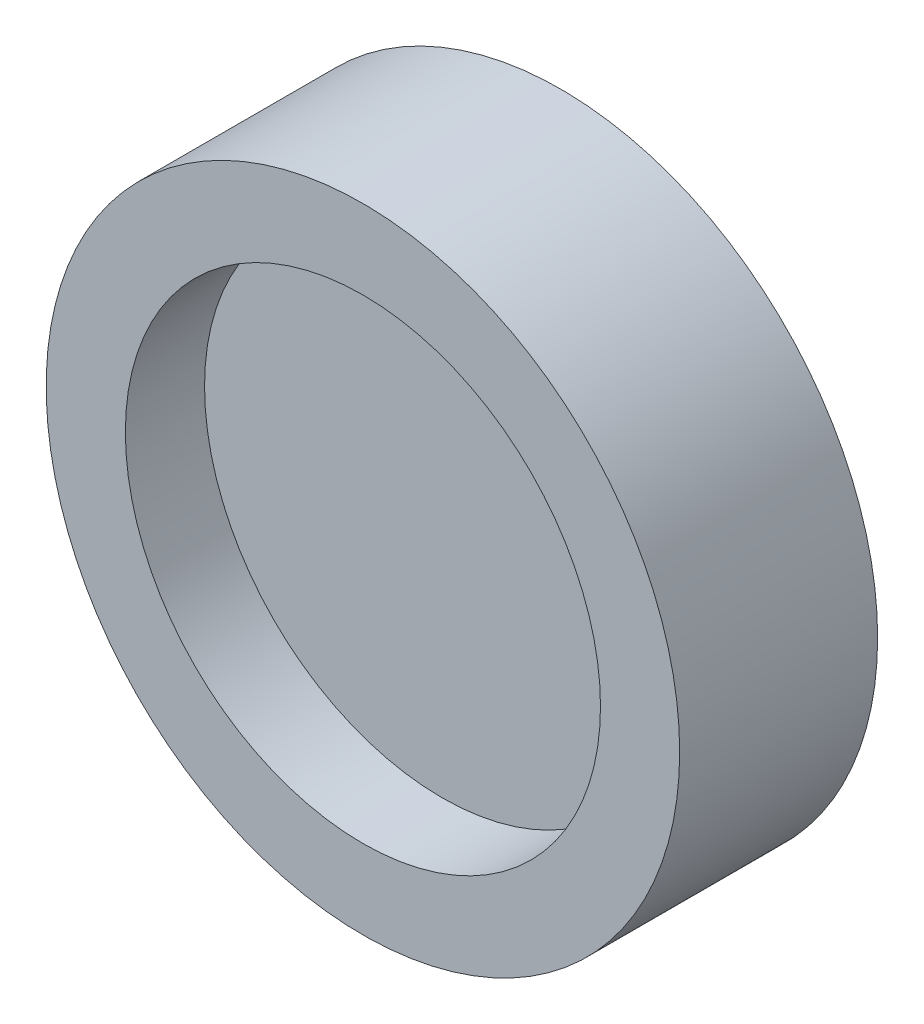
SolidWorks part; units mm, degrees
ref_plane "Спереди" through (0, 0, 0) normal (0, 0, 1) x (1, 0, 0)
ref_plane "Сверху" through (0, 0, 0) normal (0, 1, 0) x (1, 0, 0)
ref_plane "Справа" through (0, 0, 0) normal (1, 0, 0) x (0, 0, -1)
sketch "Эскиз1" plane through (0, 0, 0) normal (0, 0, 1) x (1, 0, 0)
  circle A0 centre (0, 0) radius 8
extrude "Бобышка-Вытянуть1" add sketch "Эскиз1" along normal blind 5
sketch "Эскиз2" plane through (0, 0, 5) normal (0, 0, 1) x (1, 0, 0)
  circle A0 centre (0, 0) radius 6
extrude "Вырез-Вытянуть1" cut sketch "Эскиз2" against normal blind 2
